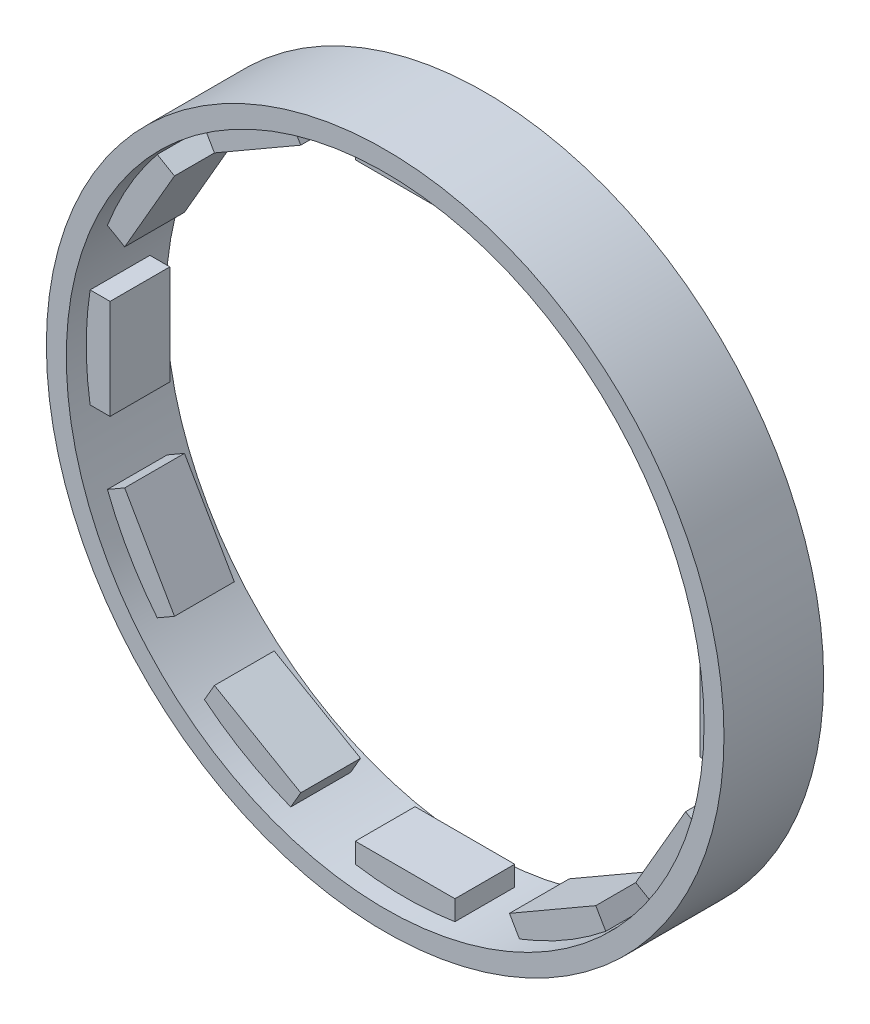
SolidWorks part; units mm, degrees
ref_plane "Front Plane" through (0, 0, 0) normal (0, 0, 1) x (1, 0, 0)
ref_plane "Top Plane" through (0, 0, 0) normal (0, 1, 0) x (1, 0, 0)
ref_plane "Right Plane" through (0, 0, 0) normal (1, 0, 0) x (0, 0, -1)
sketch "Sketch15" plane through (0, 0, 0) normal (0, 0, 1) x (1, 0, 0)
  line L0 (0, -21.7768) -> (0, 21.7768) construction
  circle A0 centre (0, 0) radius 17
  circle A1 centre (0, 0) radius 16
  point P8 (0, 0)
  dimension "D1" = 34
  dimension "D2" = 1
extrude "Boss-Extrude1" add sketch "Sketch15" along normal blind 5
ref_plane "Plane4" through (0, 0, 2.5) normal (0, 0, -1) x (-1, 0, 0)
sketch "Sketch16" plane through (0, 0, 2.5) normal (0, 0, -1) x (-1, 0, 0)
  line L0 (0, -20.1287) -> (0, 20.1287) construction
  line L3 (2.5, 15.8035) -> (2.5, 14.8035)
  line L4 (2.5, 14.8035) -> (-2.5, 14.8035)
  line L5 (-2.5, 15.8035) -> (-2.5, 14.8035)
  line L6 (2.5, 15.8035) -> (-2.5, 14.8035) construction
  line L7 (2.5, 14.8035) -> (-2.5, 15.8035) construction
  circle A0 centre (0, 0) radius 16 construction
  circle A1 centre (0, 0) radius 16
  point P4 (0, 0)
  point P8 (0, 15.3035)
  point P13 (0, 0)
  point P14 (-2.214, 15.8461)
  point P15 (0, 0)
  dimension "D1" = 1
  dimension "D2" = 5
extrude "Boss-Extrude2" add sketch "Sketch16" along normal mid plane 3
pattern_circular "CirPattern1" count 12 over 360 about axis through (0, 0, 0) along (0, 0, 1) of "Boss-Extrude2"
